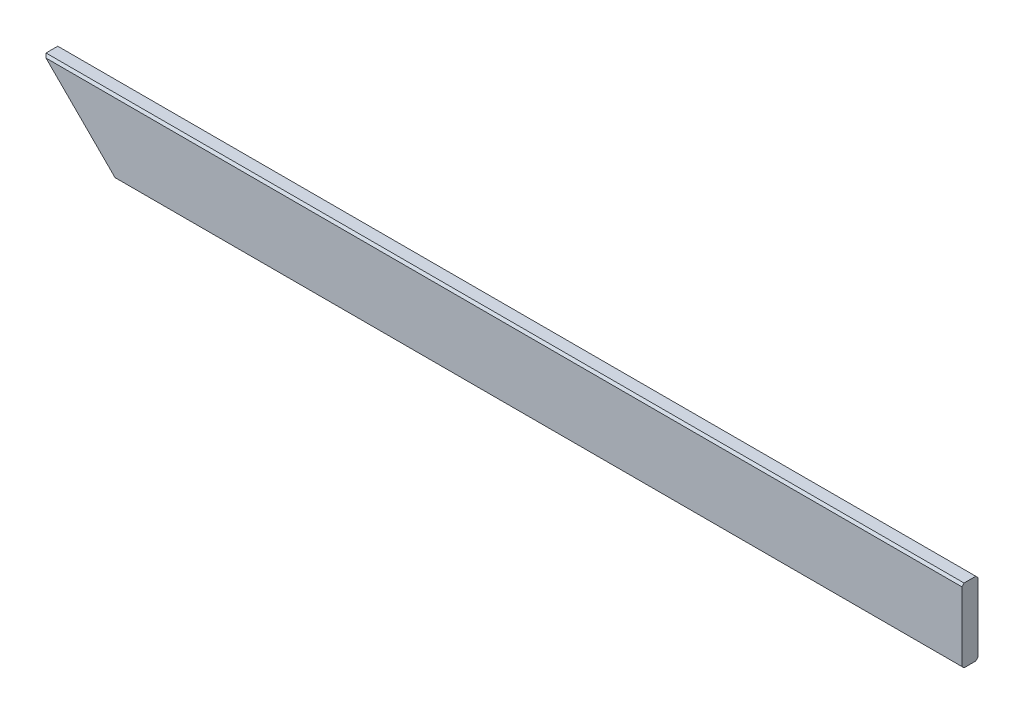
SolidWorks part; units mm, degrees
ref_plane "Plan de face" through (0, 0, 0) normal (0, 0, 1) x (1, 0, 0)
ref_plane "Plan de dessus" through (0, 0, 0) normal (0, 1, 0) x (1, 0, 0)
ref_plane "Plan de droite" through (0, 0, 0) normal (1, 0, 0) x (0, 0, -1)
sketch "Esquisse1" plane through (0, 0, 0) normal (0, 0, 1) x (1, 0, 0)
  line L1 (0, 0) -> (1950, 0)
  line L2 (0, 0) -> (0, 100)
  line L3 (0, 100) -> (1950, 100)
  line L4 (1950, 0) -> (1950, 100)
  dimension "D1" = 1950
  dimension "D2" = 100
extrude "Boss.-Extru.1" add sketch "Esquisse1" along normal blind 22
sketch "Esquisse2" plane through (0, 0, 0) normal (0, 0, -1) x (-1, 0, 0)
  line L0 (0, 0) -> (-800, 0)
  line L1 (0, 0) -> (-1950, 0) construction
  line L2 (-800, 0) -> (-700, 100)
  line L3 (-1950, 100) -> (0, 100) construction
  line L4 (-700, 100) -> (0, 100)
  line L5 (-1950, 0) -> (-1950, 100) construction
  line L6 (0, 0) -> (0, 100)
  dimension "D1" = 45
  dimension "D2" = 1150
extrude "Enlèv. mat.-Extru.1" cut sketch "Esquisse2" against normal through all both and the other way through all
chamfer "Chanfrein1" distance 3 angle 45 4 edges at (1375, 0, 0) (1375, 0, 22) (1325, 100, 0) (1325, 100, 22)
sketch "Esquisse3" [suppressed] plane through (0, 0, 0) normal (0, 0, -1) x (-1, 0, 0)
  line L0 (-1950, 120) -> (-730, 120) construction
  line L1 (-1950, 0) -> (-1150, 0)
  line L2 (-1950, 0) -> (-1950, 120)
  line L3 (-1950, 120) -> (-1150, 120)
  line L4 (-1150, 0) -> (-1150, 120)
  dimension "D1" = 1050
extrude "Enlèv. mat.-Extru.2" [suppressed] cut sketch "Esquisse3" against normal through all both and the other way through all
